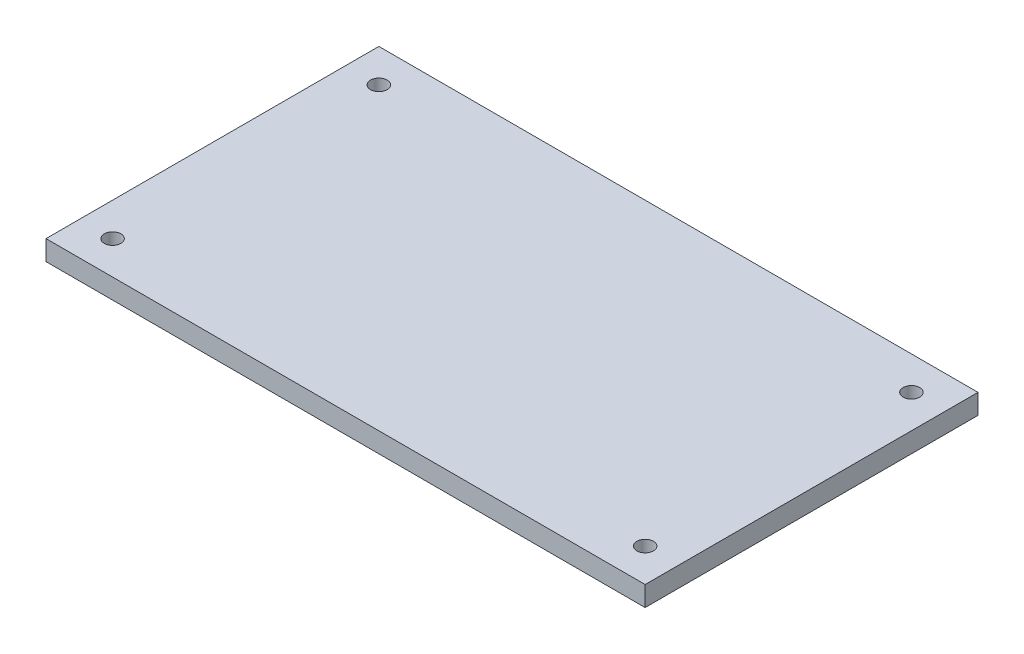
SolidWorks part; units mm, degrees
ref_plane "Спереди" through (0, 0, 0) normal (0, 0, 1) x (1, 0, 0)
ref_plane "Сверху" through (0, 0, 0) normal (0, 1, 0) x (1, 0, 0)
ref_plane "Справа" through (0, 0, 0) normal (1, 0, 0) x (0, 0, -1)
sketch "Эскиз1" plane through (0, 0, 0) normal (0, 1, 0) x (1, 0, 0)
  line L1 (-11.1207, 30.2802) -> (78.8793, 30.2802)
  line L2 (-11.1207, 30.2802) -> (-11.1207, -19.7198)
  line L3 (-11.1207, -19.7198) -> (78.8793, -19.7198)
  line L4 (78.8793, 30.2802) -> (78.8793, -19.7198)
  dimension "D1" = 50
  dimension "D2" = 90
extrude "Бобышка-Вытянуть1" add sketch "Эскиз1" along normal blind 3
sketch "Эскиз2" plane through (0, 3, 0) normal (0, 1, 0) x (1, 0, 0)
  line L0 (78.8793, 30.2802) -> (-11.1207, 30.2802) construction
  line L1 (78.8793, -19.7198) -> (78.8793, 30.2802) construction
  line L2 (-11.1207, 30.2802) -> (-11.1207, -19.7198) construction
  line L3 (-11.1207, -19.7198) -> (78.8793, -19.7198) construction
  circle A0 centre (-6.1207, 25.2802) radius 1.25
  circle A1 centre (73.8793, 25.2802) radius 1.25
  circle A2 centre (73.8793, -14.7198) radius 1.25
  circle A3 centre (-6.1207, -14.7198) radius 1.25
  dimension "D1" = 2.5
  dimension "D2" = 2.5
  dimension "D3" = 2.5
  dimension "D4" = 2.5
  dimension "D5" = 5
  dimension "D6" = 5
  dimension "D7" = 5
  dimension "D8" = 5
  dimension "D9" = 5
  dimension "D10" = 5
  dimension "D11" = 5
  dimension "D12" = 5
extrude "Вырез-Вытянуть1" cut sketch "Эскиз2" against normal blind 3
